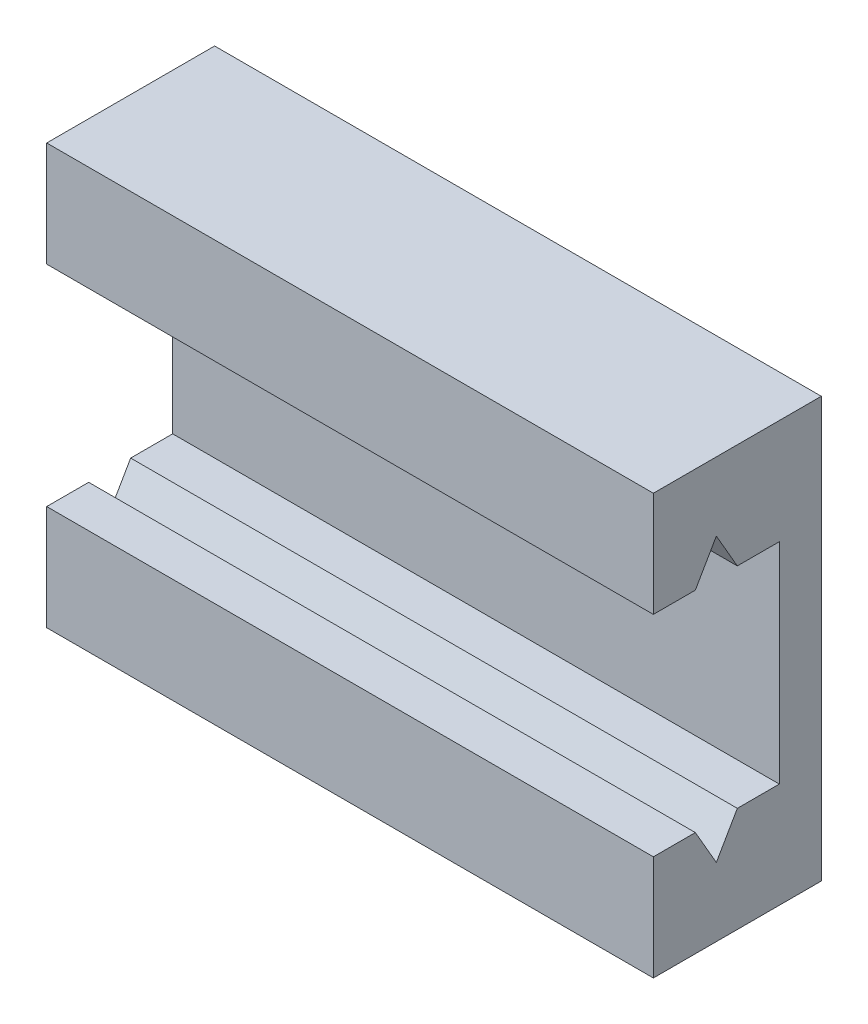
SolidWorks part; units mm, degrees
ref_plane "前视基准面" through (0, 0, 0) normal (0, 0, 1) x (1, 0, 0)
ref_plane "上视基准面" through (0, 0, 0) normal (0, 1, 0) x (1, 0, 0)
ref_plane "右视基准面" through (0, 0, 0) normal (1, 0, 0) x (0, 0, -1)
other "Configuration Table"
sketch "草图1" plane through (0, 0, 0) normal (0, 0, 1) x (1, 0, 0)
  line L1 (0, 0) -> (28.9, 0)
  line L2 (0, 0) -> (0, 20)
  line L3 (0, 20) -> (28.9, 20)
  line L4 (28.9, 0) -> (28.9, 20)
  dimension "D1" = 20
  dimension "D2" = 28.9
extrude "凸台-拉伸1" add sketch "草图1" along normal blind 8
sketch "草图3" plane through (28.9, 0, 0) normal (1, 0, 0) x (0, 0, -1)
  line L0 (-8, 15) -> (-6, 15)
  line L1 (-8, 0) -> (-8, 20) construction
  line L2 (-6, 15) -> (-5, 16.7321)
  line L3 (-5, 16.7321) -> (-4, 15)
  line L4 (-4, 15) -> (-2, 15)
  line L5 (-2, 15) -> (-2, 5)
  line L6 (-8, 10) -> (49992, 10) construction
  line L7 (-8, 15) -> (-8, 5)
  line L8 (-4, 5) -> (-2, 5)
  line L9 (-5, 3.2679) -> (-4, 5)
  line L10 (-6, 5) -> (-5, 3.2679)
  line L11 (-8, 5) -> (-6, 5)
  point P10 (-8, 10)
  point P13 (-8, 10)
  point P14 (-2, 10)
  point P17 (0, 0)
  dimension "D1" = 2
  dimension "D2" = 2
  dimension "D3" = 60
  dimension "D4" = 6
  dimension "D5" = 5
  dimension "D6" = 120
  dimension "D7" = 2
extrude "切除-拉伸9" cut sketch "草图3" against normal up to next
sketch "草图2" plane through (0, 0, 0) normal (0, 0, -1) x (-1, 0, 0)
  line L0 (-14.45, 20) -> (-14.45, -49980) construction
  line L1 (-28.9, 20) -> (0, 20) construction
  line L2 (0, 10) -> (-50000, 10) construction
  line L3 (0, 20) -> (0, 0) construction
  line L5 (-19.45, 2.5) -> (-9.45, 2.5) construction
  line L6 (-19.45, 2.5) -> (-19.45, 17.5) construction
  line L7 (-19.45, 17.5) -> (-9.45, 17.5) construction
  line L8 (-9.45, 2.5) -> (-9.45, 17.5) construction
  line L9 (-19.45, 2.5) -> (-9.45, 17.5) construction
  line L10 (-19.45, 17.5) -> (-9.45, 2.5) construction
  circle A0 centre (-19.45, 17.5) radius 1.5
  circle A1 centre (-9.45, 17.5) radius 1.5
  circle A2 centre (-19.45, 2.5) radius 1.5
  circle A3 centre (-9.45, 2.5) radius 1.5
  point P4 (-14.45, 20)
  point P9 (0, 10)
  point P10 (-14.45, 10)
  dimension "D1" = 10
  dimension "D2" = 15
extrude "切除-拉伸1" cut sketch "草图2" against normal blind 4
